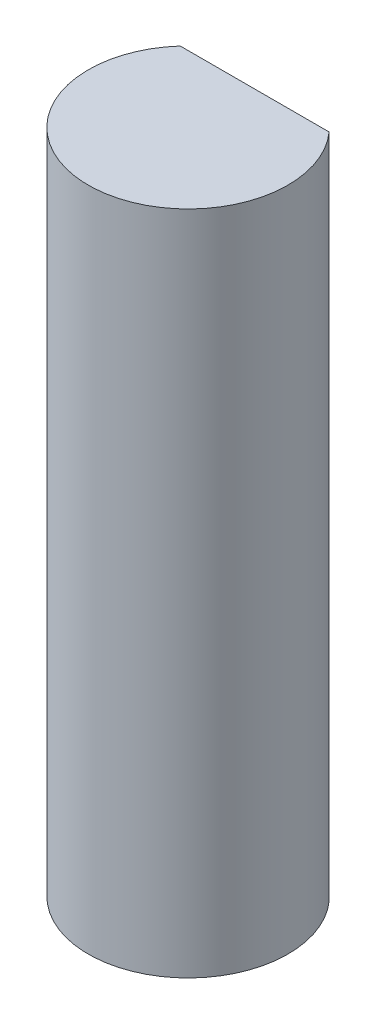
SolidWorks part; units mm, degrees
ref_plane "Front Plane" through (0, 0, 0) normal (0, 0, 1) x (1, 0, 0)
ref_plane "Top Plane" through (0, 0, 0) normal (0, 1, 0) x (1, 0, 0)
ref_plane "Right Plane" through (0, 0, 0) normal (1, 0, 0) x (0, 0, -1)
sketch "Sketch1" plane through (0, 0, 0) normal (0, 1, 0) x (1, 0, 0)
  line L0 (-2.1438, 1) -> (3.2909, 1)
  circle A0 centre (0, 0) radius 1.5
  dimension "D1" = 3
  dimension "D2" = 1
extrude "Boss-Extrude1" add sketch "Sketch1" along normal blind 10 contours L0 A0
